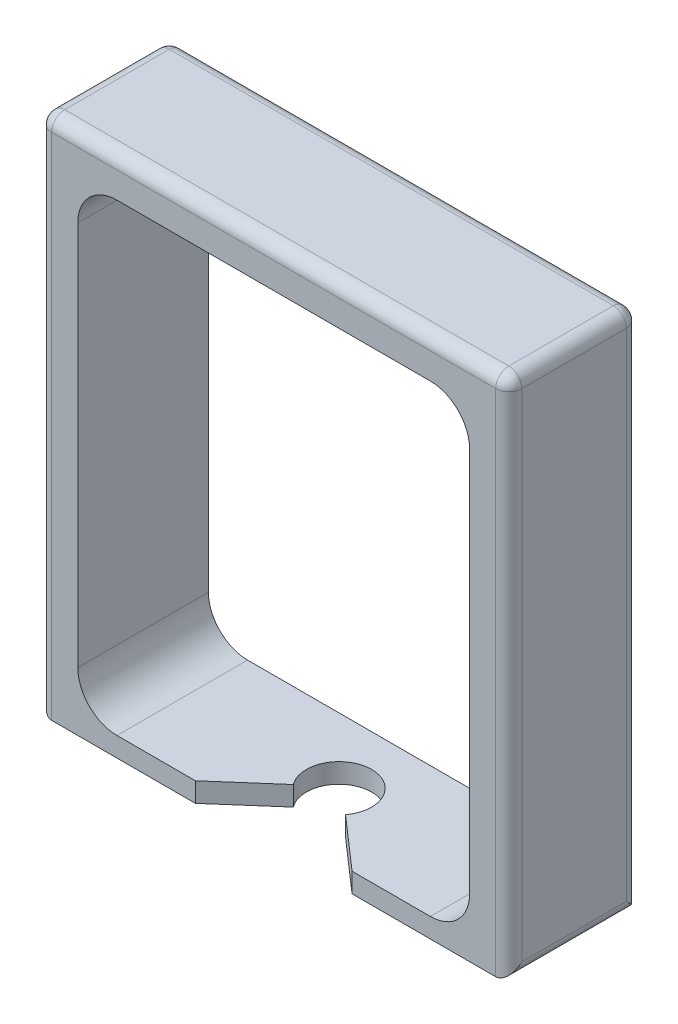
SolidWorks part; units mm, degrees
ref_plane "Front Plane" through (0, 0, 0) normal (0, 0, 1) x (1, 0, 0)
ref_plane "Top Plane" through (0, 0, 0) normal (0, 1, 0) x (1, 0, 0)
ref_plane "Right Plane" through (0, 0, 0) normal (1, 0, 0) x (0, 0, -1)
sketch "Sketch1" plane through (0, 0, 0) normal (0, 0, 1) x (1, 0, 0)
  line L1 (-15, 17) -> (15, 17)
  line L2 (-15, 17) -> (-15, -18.5)
  line L3 (-15, -18.5) -> (15, -18.5)
  line L4 (15, 17) -> (15, -18.5)
  line L5 (-18, 20) -> (18, 20)
  line L6 (-18, 20) -> (-18, -20)
  line L7 (-18, -20) -> (18, -20)
  line L8 (18, 20) -> (18, -20)
  point P8 (-18, 0)
  point P9 (0, 20)
  dimension "D1" = 3
  dimension "D2" = 3
  dimension "D3" = 3
  dimension "D4" = 1.5
  dimension "D5" = 30
  dimension "D6" = 40
extrude "Boss-Extrude1" add sketch "Sketch1" along normal blind 10
sketch "Sketch2" plane through (0, -20, 0) normal (0, -1, 0) x (1, 0, 0)
  line L0 (-6, 10) -> (-2, 6.5)
  line L1 (-18, 10) -> (18, 10) construction
  line L2 (6, 10) -> (2, 6.5)
  line L3 (-18, 10) -> (-18, 0) construction
  line L4 (-6, 10) -> (6, 10)
  arc A0 (-2, 6.5) -> (2, 6.5) centre (0, 5) ccw
  point P15 (-18, 5)
  dimension "D1" = 2.5
  dimension "D2" = 12
  dimension "D3" = 3.5
extrude "Cut-Extrude2" cut sketch "Sketch2" against normal up to next
fillet "Fillet1" radius 3 4 edges at (15, 17, 5) (-15, 17, 5) (15, -18.5, 5) (-15, -18.5, 5)
fillet "Fillet2" radius 1 10 edges at (-18, -20, 5) (18, -20, 5) (18, 0, 10) (18, 0, 0) (-18, 0, 0) (-18, 0, 10) (0, 20, 0) (0, 20, 10) (-18, 20, 5) (18, 20, 5)
